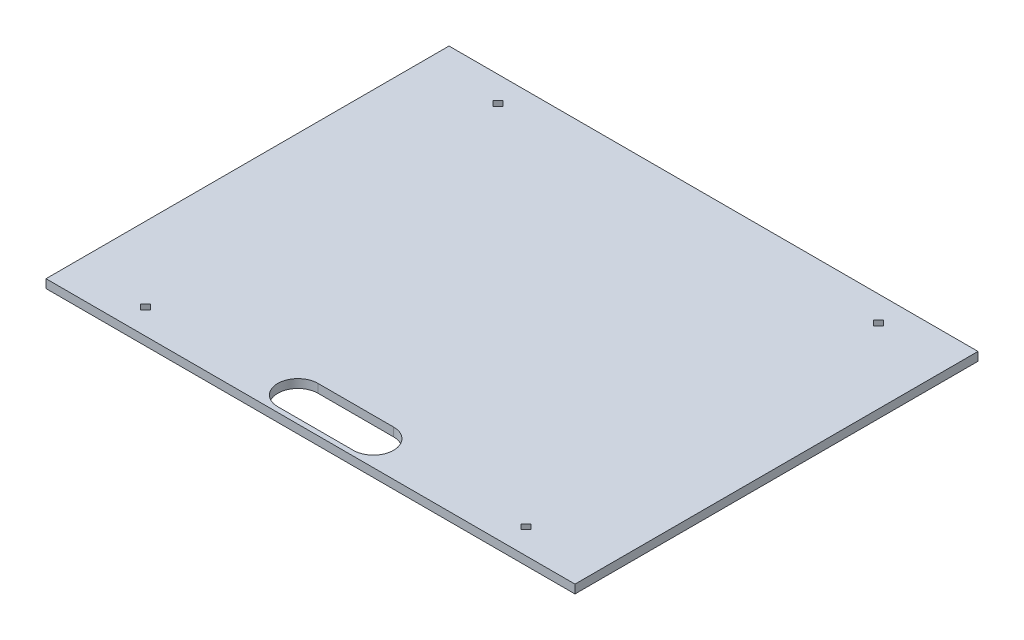
SolidWorks part; units mm, degrees
ref_plane "前视基准面" through (0, 0, 0) normal (0, 0, 1) x (1, 0, 0)
ref_plane "上视基准面" through (0, 0, 0) normal (0, 1, 0) x (1, 0, 0)
ref_plane "右视基准面" through (0, 0, 0) normal (1, 0, 0) x (0, 0, -1)
other "Configuration Table"
sketch "草图1" plane through (0, 0, 0) normal (0, 1, 0) x (1, 0, 0)
  line L0 (-81.322, 0) -> (69.384, 0) construction
  line L1 (-52.5, 40) -> (52.5, 40)
  line L2 (-52.5, 40) -> (-52.5, -40)
  line L3 (-52.5, -40) -> (52.5, -40)
  line L4 (52.5, 40) -> (52.5, -40)
  line L5 (-52.5, 40) -> (52.5, -40) construction
  line L6 (-52.5, -40) -> (52.5, 40) construction
  line L7 (0, 66.6909) -> (0, -62.4569) construction
  line L8 (38.7593, 35) -> (37.7593, 34)
  line L9 (-37.7593, 34) -> (-36.7593, 35)
  line L10 (-36.7593, 35) -> (-37.7593, 36)
  line L11 (-37.7593, 36) -> (-38.7593, 35)
  line L12 (-38.7593, 35) -> (-37.7593, 34)
  line L13 (37.7593, 36) -> (38.7593, 35)
  line L14 (36.7593, 35) -> (37.7593, 36)
  line L15 (37.7593, 34) -> (36.7593, 35)
  line L16 (37.7593, -36) -> (38.7593, -35)
  line L17 (36.7593, -35) -> (37.7593, -36)
  line L18 (37.7593, -34) -> (36.7593, -35)
  line L19 (38.7593, -35) -> (37.7593, -34)
  line L20 (-38.7593, -35) -> (-37.7593, -34)
  line L21 (-37.7593, -36) -> (-38.7593, -35)
  line L22 (-36.7593, -35) -> (-37.7593, -36)
  line L23 (-37.7593, -34) -> (-36.7593, -35)
  line L27 (-7.5, -35) -> (7.5, -35) construction
  line L28 (-7.5, -39) -> (7.5, -39)
  line L29 (-7.5, -31) -> (7.5, -31)
  circle A0 centre (-37.7593, 35) radius 0.7071 construction
  arc A3 (-7.5, -39) -> (-7.5, -31) centre (-7.5, -35) cw
  arc A4 (7.5, -31) -> (7.5, -39) centre (7.5, -35) cw
  point P0 (0, 0)
  point P38 (0, -35)
  dimension "D1" = 105
  dimension "D2" = 80
  dimension "D3" = 35
  dimension "D4" = 2
extrude "凸台-拉伸1" add sketch "草图1" along normal blind 1.7023
